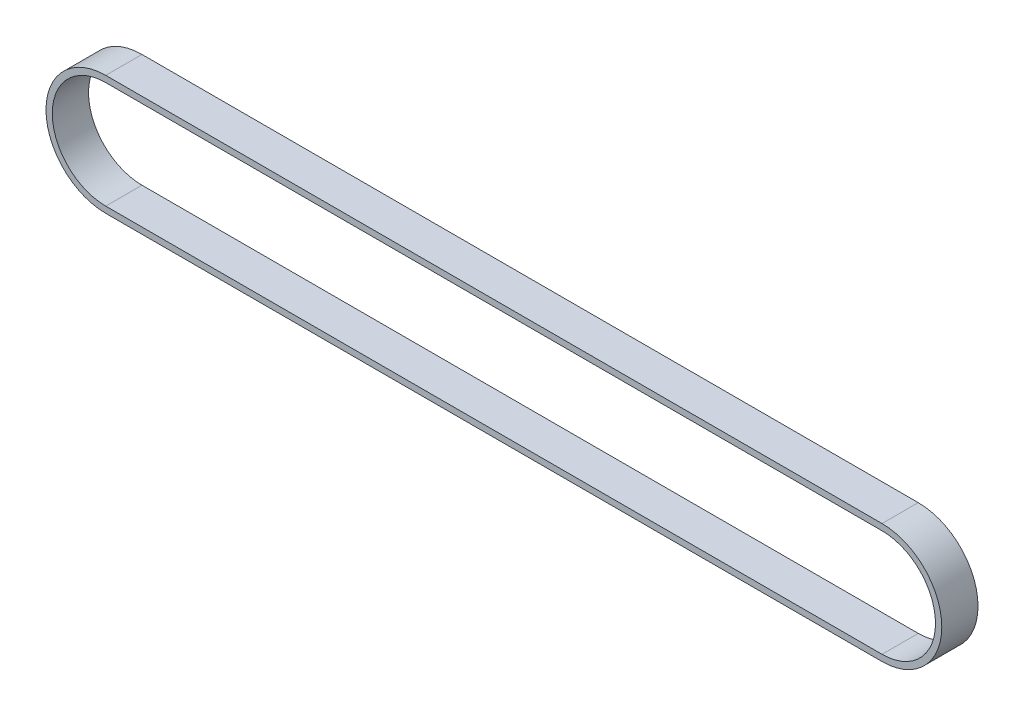
SolidWorks part; units mm, degrees
ref_plane "Front Plane" through (0, 0, 0) normal (0, 0, 1) x (1, 0, 0)
ref_plane "Top Plane" through (0, 0, 0) normal (0, 1, 0) x (1, 0, 0)
ref_plane "Right Plane" through (0, 0, 0) normal (1, 0, 0) x (0, 0, -1)
sketch "Sketch1" plane through (0, 0, 0) normal (0, 0, 1) x (1, 0, 0)
  line L3 (0, 10.56) -> (137.17, 10.56)
  line L4 (0, -10.56) -> (137.17, -10.56)
  arc A7 (0, 10.56) -> (0, -10.56) centre (0, 0) ccw
  arc A8 (137.17, -10.56) -> (137.17, 10.56) centre (137.17, 0) ccw
extrude "Boss-Extrude1" add sketch "Sketch1" along normal blind 6.4
sketch "Sketch2" plane through (0, 0, 6.4) normal (0, 0, 1) x (1, 0, 0)
  line L4 (0, 9.45) -> (137.17, 9.45)
  line L5 (0, -9.45) -> (137.17, -9.45)
  arc A6 (0, 9.45) -> (0, -9.45) centre (0, 0) ccw
  arc A7 (137.17, -9.45) -> (137.17, 9.45) centre (137.17, 0) ccw
extrude "Cut-Extrude1" cut sketch "Sketch2" against normal through all
